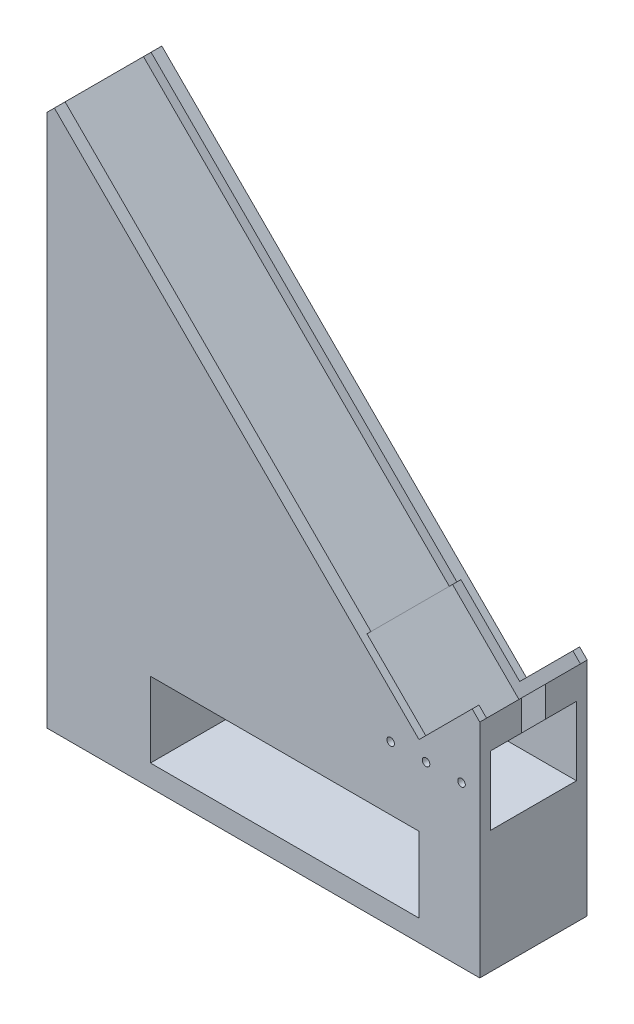
SolidWorks part; units mm, degrees
material "PEI"
ref_plane "Front Plane" through (0, 0, 0) normal (0, 0, 1) x (1, 0, 0)
ref_plane "Top Plane" through (0, 0, 0) normal (0, 1, 0) x (1, 0, 0)
ref_plane "Right Plane" through (0, 0, 0) normal (1, 0, 0) x (0, 0, -1)
sketch "Sketch2" plane through (0, 0, 0) normal (0, 0, 1) x (1, 0, 0)
  line L0 (218.2754, 103.1635) -> (218.2754, 0)
  line L1 (0, 44.0395) -> (0, 248.1204)
  line L2 (0, 248.1204) -> (173.2412, 74.8792)
  line L3 (173.2412, 74.8792) -> (201.5254, 103.1635)
  line L4 (201.5254, 103.1635) -> (218.2754, 103.1635)
  line L5 (173.2412, 74.8792) -> (200.1819, 101.82) construction
  line L6 (200.1819, 101.82) -> (173.2412, 128.7607) construction
  line L7 (173.2412, 128.7607) -> (146.3004, 101.82) construction
  line L8 (0, 44.0395) -> (0, 0)
  line L9 (0, 0) -> (218.2754, 0)
  point P9 (186.7115, 115.2904)
  dimension "D1" = 40
  dimension "D2" = 90
  dimension "D3" = 115.2904
  dimension "D4" = 16.75
  dimension "D5" = 38.1
  dimension "D6" = 45
  dimension "D7" = 245
extrude "Boss-Extrude1" add sketch "Sketch2" along normal blind 50
sketch "Sketch7" plane through (0, 0, 0) normal (-1, 0, 0) x (0, 0, 1)
  line L0 (50, 0) -> (0, 0) construction
  line L1 (5, 0) -> (5, 243.1204)
  line L2 (5, 243.1204) -> (45, 243.1204)
  line L3 (45, 243.1204) -> (45, 0)
  line L4 (0, 248.1204) -> (0, 0) construction
  line L5 (50, 248.1204) -> (0, 248.1204) construction
  line L6 (50, 248.1204) -> (50, 0) construction
  line L7 (5, 0) -> (45, 0)
  dimension "D1" = 5
  dimension "D2" = 5
  dimension "D3" = 5
extrude "Cut-Extrude1" cut sketch "Sketch7" against normal offset from surface 10 up to face at (86.6206, 161.4998, 25)
sketch "Sketch8" plane through (218.2754, 0, 0) normal (1, 0, 0) x (0, 0, -1)
  line L0 (-45, 15.7028) -> (-45, 95.9135)
  line L1 (-5, 15.7028) -> (-5, 95.9135)
  line L2 (-5, 95.9135) -> (-45, 95.9135)
  line L3 (-45, 15.7028) -> (-5, 15.7028)
  dimension "D1" = 7.25
extrude "Cut-Extrude2" cut sketch "Sketch8" against normal offset from surface (9.8579 mm away) 10
sketch "Sketch10" plane through (0, 0, 50) normal (0, 0, 1) x (1, 0, 0)
  line L0 (0, 248.1204) -> (3.5355, 251.6559)
  line L2 (3.5355, 251.6559) -> (173.2412, 81.9503)
  line L3 (201.5254, 103.1635) -> (197.9899, 106.699)
  line L4 (173.2412, 81.9503) -> (197.9899, 106.699)
  line L5 (0, 248.1204) -> (173.2412, 74.8792)
  line L6 (201.5254, 103.1635) -> (173.2412, 74.8792)
  dimension "D1" = 5
  dimension "D2" = 5
extrude "Boss-Extrude2" add sketch "Sketch10" against normal blind 5
sketch "Sketch11" plane through (0, 0, 0) normal (0, 0, -1) x (-1, 0, 0)
  line L0 (-201.5254, 103.1635) -> (-197.9899, 106.699)
  line L1 (-197.9899, 106.699) -> (-173.2412, 81.9503)
  line L2 (-173.2412, 81.9503) -> (-3.5355, 251.6559)
  line L3 (-3.5355, 251.6559) -> (0, 248.1204)
  line L4 (0, 248.1204) -> (-173.2412, 74.8792)
  line L5 (-173.2412, 74.8792) -> (-201.5254, 103.1635)
extrude "Boss-Extrude3" add sketch "Sketch11" against normal blind 5
sketch "Sketch12" plane through (49.181, -49.181, 0) normal (-0.7071, 0.7071, 0) x (0, 0, 1)
  line L0 (25, 188.4476) -> (25, 238.4476) construction
  line L1 (30.5, 188.4476) -> (19.5, 188.4476)
  line L2 (30.5, 188.4476) -> (30.5, 238.4476)
  line L3 (30.5, 238.4476) -> (19.5, 238.4476)
  line L4 (19.5, 188.4476) -> (19.5, 238.4476)
  line L5 (19.5, 213.4476) -> (30.5, 213.4476) construction
  line L6 (45, 175.4476) -> (5, 175.4476) construction
  line L7 (25, 175.4476) -> (25, 215.4476) construction
  line L8 (45, 215.4476) -> (5, 215.4476) construction
  dimension "D1" = 11
  dimension "D2" = 50
  dimension "D3" = 13
extrude "Cut-Extrude3" cut sketch "Sketch12" against normal blind 20
sketch "Sketch13" plane through (218.2754, 0, 0) normal (1, 0, 0) x (0, 0, -1)
  line L0 (0, 0) -> (0, 103.1635) construction
  line L1 (-50, 0) -> (-50, 103.1635) construction
  line L2 (0, 0) -> (0, 57)
  line L3 (-50, 0) -> (-50, 57)
  line L5 (0, 0) -> (-50, 0)
  line L6 (-50, 57) -> (0, 57)
  dimension "D1" = 57
extrude "Boss-Extrude4" add sketch "Sketch13" against normal up to surface (218.2754 mm away) up to face at (0, 146.0438, 25)
sketch "Sketch14" plane through (124.0602, 124.0602, 0) normal (0.7071, 0.7071, 0) x (0, 0, -1)
  line L2 (-3.15, -69.5524) -> (-3.15, -25.8524)
  line L6 (-3.15, -69.5524) -> (-46.85, -69.5524)
  line L8 (-45, -69.5524) -> (-5, -69.5524) construction
  line L9 (-45, -69.5524) -> (-5, -69.5524)
  line L10 (-3.15, -25.8524) -> (-46.85, -25.8524)
  line L11 (-46.85, -25.8524) -> (-46.85, -69.5524)
  point P8 (-25, -69.5524)
  point P9 (-25, -69.5524)
  line M5 (-45, -69.5524) -> (-5, -69.5524)
  line M6 (-5, -69.5524) -> (-5, 175.4476)
  line M8 (-45, 175.4476) -> (-45, -69.5524)
  dimension "D1" = 43.7
extrude "Cut-Extrude5" cut sketch "Sketch14" against normal blind 0.48 and the other way through all contours L10 M6 M8 M5 | L10 L11 L6 M8 | L2 L10 L6 M6
sketch "Sketch15" plane through (49.181, -49.181, 0) normal (-0.7071, 0.7071, 0) x (0, 0, 1)
  line L0 (46.85, 174.9676) -> (3.15, 174.9676) construction
  line L1 (46.85, 174.9676) -> (3.15, 174.9676)
  line L2 (25, 174.9676) -> (25, 179.9676) construction
  line L3 (30.5, 174.9676) -> (30.5, 179.9676)
  line L4 (30.5, 179.9676) -> (19.5, 179.9676)
  line L5 (19.5, 179.9676) -> (19.5, 174.9676)
  point P9 (25, 179.9676)
  line M13 (3.15, 174.9676) -> (46.85, 174.9676)
  dimension "D1" = 5
  dimension "D2" = 11
extrude "Cut-Extrude6" cut sketch "Sketch15" along normal up to surface (29.805 mm away) contours L2 L3 L4 M13 | L1 L2 L4 L5
sketch "Sketch16" plane through (0, 0, 50) normal (0, 0, 1) x (1, 0, 0)
  line L0 (48.2412, 10) -> (48.2412, 45)
  line L1 (48.2412, 45) -> (173.2412, 45)
  line L2 (173.2412, 45) -> (173.2412, 10)
  line L3 (173.2412, 10) -> (48.2412, 10)
  line L8 (0, 248.1204) -> (0, 0)
  line L9 (0, 0) -> (218.2754, 0)
  line L10 (218.2754, 0) -> (218.2754, 103.1635)
  line L11 (218.2754, 103.1635) -> (201.5254, 103.1635)
  line L12 (201.5254, 103.1635) -> (197.9899, 106.699)
  line L13 (197.9899, 106.699) -> (173.2412, 81.9503)
  line L14 (173.2412, 81.9503) -> (3.5355, 251.6559)
  line L15 (3.5355, 251.6559) -> (0, 248.1204)
  line L16 (0, 248.1204) -> (0, 0) construction
  line L17 (0, 0) -> (218.2754, 0) construction
  line L18 (218.2754, 0) -> (218.2754, 103.1635) construction
  line L19 (218.2754, 103.1635) -> (201.5254, 103.1635) construction
  line L20 (201.5254, 103.1635) -> (197.9899, 106.699) construction
  line L21 (197.9899, 106.699) -> (173.2412, 81.9503) construction
  line L22 (173.2412, 81.9503) -> (3.5355, 251.6559) construction
  line L23 (3.5355, 251.6559) -> (0, 248.1204) construction
  dimension "D2" = 125
  dimension "D3" = 35
  dimension "D4" = 10
  dimension "D1" = 0
extrude "Cut-Extrude7" cut sketch "Sketch16" against normal up to surface (45 mm away) up to face at (136.3683, 100.0904, 5)
sketch "Sketch17" plane through (0, 0, 5) normal (0, 0, 1) x (1, 0, 0)
  line L0 (48.2412, 27.5) -> (173.2412, 27.5) construction
  line L4 (48.2412, 10) -> (173.2412, 10)
  line L5 (173.2412, 10) -> (173.2412, 45)
  line L6 (173.2412, 45) -> (48.2412, 45)
  line L7 (48.2412, 45) -> (48.2412, 10)
  line L8 (48.2412, 10) -> (173.2412, 10)
  line L9 (173.2412, 10) -> (173.2412, 45)
  line L10 (173.2412, 45) -> (48.2412, 45)
  line L11 (48.2412, 45) -> (48.2412, 10)
  circle A0 centre (75.7412, 27.5) radius 1.75
  circle A1 centre (110.7412, 27.5) radius 1.75
  circle A2 centre (145.7412, 27.5) radius 1.75
  point P8 (110.7412, 27.5)
  dimension "D3" = 3.5
  dimension "D2" = 35
  dimension "D1" = 0
  dimension "D4" = 2
extrude "Cut-Extrude8" cut sketch "Sketch17" against normal up to surface (5 mm away) contours A0 L0 | L0 A0 | A1 L0 | L0 A1 | A2 L0 | L0 A2 up to face at (126.6054, 111.8441, 0)
sketch "Sketch18" plane through (218.2754, 0, 0) normal (1, 0, 0) x (0, 0, -1)
  line L12 (-5, 95.9135) -> (-5, 57)
  line L13 (-5, 57) -> (-45, 57)
  line L14 (-45, 57) -> (-45, 95.9135)
  line L15 (-45, 95.9135) -> (-30.5, 95.9135)
  line L16 (-30.5, 95.9135) -> (-30.5, 103.1635)
  line L17 (-30.5, 103.1635) -> (-50, 103.1635)
  line L18 (-50, 103.1635) -> (-50, 0)
  line L19 (-50, 0) -> (0, 0)
  line L20 (0, 0) -> (0, 103.1635)
  line L21 (0, 103.1635) -> (-19.5, 103.1635)
  line L22 (-19.5, 103.1635) -> (-19.5, 95.9135)
  line L23 (-19.5, 95.9135) -> (-5, 95.9135)
  line L24 (-5, 95.9135) -> (-5, 57)
  line L25 (-5, 57) -> (-45, 57)
  line L26 (-45, 57) -> (-45, 95.9135)
  line L27 (-45, 95.9135) -> (-30.5, 95.9135)
  line L28 (-30.5, 95.9135) -> (-30.5, 103.1635)
  line L29 (-30.5, 103.1635) -> (-50, 103.1635)
  line L30 (-50, 103.1635) -> (-50, 0)
  line L31 (-50, 0) -> (0, 0)
  line L32 (0, 0) -> (0, 103.1635)
  line L33 (0, 103.1635) -> (-19.5, 103.1635)
  line L34 (-19.5, 103.1635) -> (-19.5, 95.9135)
  line L35 (-19.5, 95.9135) -> (-5, 95.9135)
  dimension "D1" = 0
extrude "Cut-Extrude9" cut sketch "Sketch18" against normal up to vertex (16.75 mm away) up to point (201.5254, 103.1635, 46.85)
sketch "Sketch19" plane through (0, 95.9135, 0) normal (0, 1, 0) x (1, 0, 0)
  line L0 (208.4176, -45) -> (208.4176, -30.5) construction
  line L1 (208.4176, -30.5) -> (201.5254, -30.5) construction
  line L2 (201.5254, -30.5) -> (201.5254, -45) construction
  line L3 (201.5254, -45) -> (208.4176, -45) construction
  line L4 (208.4176, -19.5) -> (208.4176, -5) construction
  line L5 (208.4176, -5) -> (201.5254, -5) construction
  line L6 (201.5254, -5) -> (201.5254, -19.5) construction
  line L7 (201.5254, -19.5) -> (208.4176, -19.5) construction
  line L8 (208.4176, -45) -> (208.4176, -30.5)
  line L9 (208.4176, -30.5) -> (201.5254, -30.5)
  line L10 (201.5254, -30.5) -> (201.5254, -45)
  line L11 (201.5254, -45) -> (208.4176, -45)
  line L12 (208.4176, -19.5) -> (208.4176, -5)
  line L13 (208.4176, -5) -> (201.5254, -5)
  line L14 (201.5254, -5) -> (201.5254, -19.5)
  line L15 (201.5254, -19.5) -> (208.4176, -19.5)
extrude "Cut-Extrude10" cut sketch "Sketch19" against normal up to next
sketch "Sketch20" plane through (0, 0, 50) normal (0, 0, 1) x (1, 0, 0)
  line L0 (160.0254, 74.5) -> (193.0254, 74.5) construction
  line L1 (173.2412, 45) -> (48.2412, 45) construction
  line L7 (0, 0) -> (201.5254, 0)
  line L8 (201.5254, 0) -> (201.5254, 103.1635)
  line L9 (201.5254, 103.1635) -> (197.9899, 106.699)
  line L10 (197.9899, 106.699) -> (173.2412, 81.9503)
  line L11 (173.2412, 81.9503) -> (3.5355, 251.6559)
  line L12 (3.5355, 251.6559) -> (0, 248.1204)
  line L13 (0, 248.1204) -> (0, 0)
  line L14 (0, 0) -> (201.5254, 0)
  line L15 (201.5254, 0) -> (201.5254, 103.1635)
  line L16 (201.5254, 103.1635) -> (197.9899, 106.699)
  line L17 (197.9899, 106.699) -> (173.2412, 81.9503)
  line L18 (173.2412, 81.9503) -> (3.5355, 251.6559)
  line L19 (3.5355, 251.6559) -> (0, 248.1204)
  line L20 (0, 248.1204) -> (0, 0)
  circle A0 centre (176.5254, 74.5) radius 1.75
  circle A1 centre (160.0254, 74.5) radius 1.75
  circle A2 centre (193.0254, 74.5) radius 1.75
  point P10 (176.5254, 74.5)
  dimension "D5" = 3.5
  dimension "D2" = 33
  dimension "D3" = 29.5
  dimension "D4" = 25
  dimension "D1" = 0
extrude "Cut-Extrude11" cut sketch "Sketch20" against normal blind 5 contours A1 | A0 | A2
equation "\"D1@Sketch14\"=43.69+0.01"
